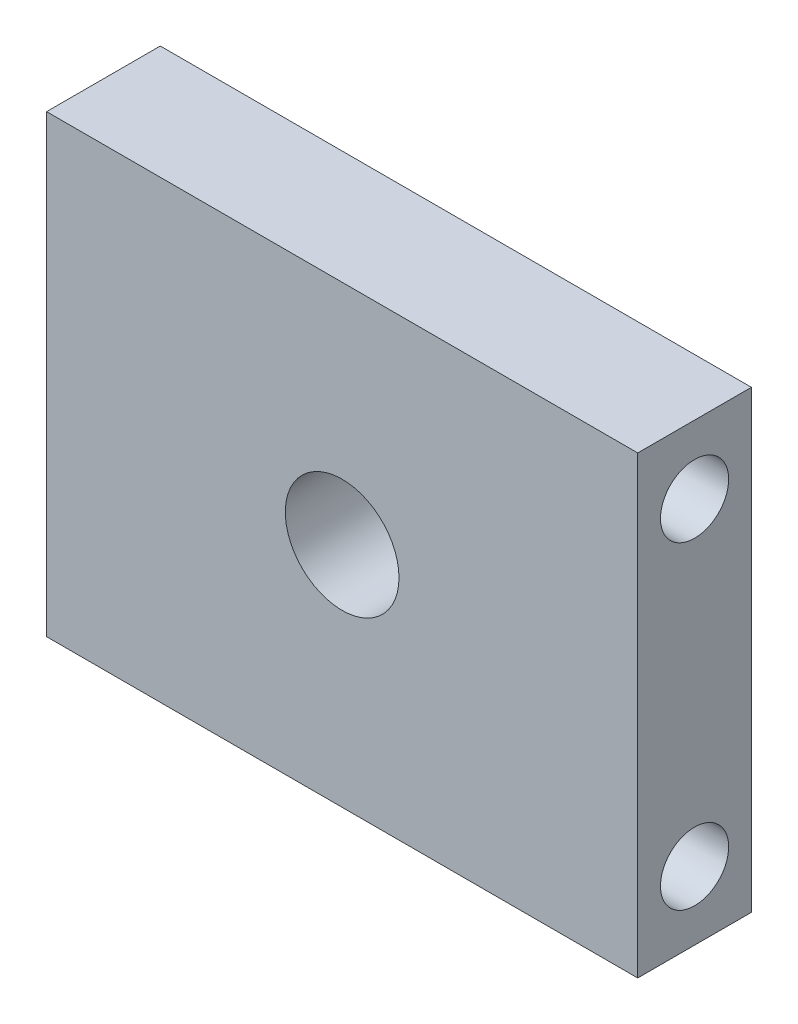
SolidWorks part; units mm, degrees
material "1060 Alloy"
ref_plane "前视基准面" through (0, 0, 0) normal (0, 0, 1) x (1, 0, 0)
ref_plane "上视基准面" through (0, 0, 0) normal (0, 1, 0) x (1, 0, 0)
ref_plane "右视基准面" through (0, 0, 0) normal (1, 0, 0) x (0, 0, -1)
sketch "Sketch1" plane through (0, 0, 0) normal (0, 0, 1) x (1, 0, 0)
  line L1 (-13, 10) -> (13, 10)
  line L2 (-13, 10) -> (-13, -10)
  line L3 (-13, -10) -> (13, -10)
  line L4 (13, 10) -> (13, -10)
  line L5 (-13, 10) -> (13, -10) construction
  line L6 (-13, -10) -> (13, 10) construction
  point P0 (0, 0)
  dimension "D1" = 26
  dimension "D2" = 20
extrude "Boss-Extrude1" add sketch "Sketch1" along normal blind 5
sketch "Sketch2" plane through (0, 0, 5) normal (0, 0, 1) x (1, 0, 0)
  circle A0 centre (0, 0) radius 2.5
extrude "Cut-Extrude1" cut sketch "Sketch2" against normal blind 5
sketch "Sketch3" plane through (-13, 0, 0) normal (-1, 0, 0) x (0, 0, 1)
  line L0 (2.5, 10) -> (2.5, -10) construction
  line L1 (5, 10) -> (0, 10) construction
  line L2 (5, -10) -> (0, -10) construction
  line L3 (0, 0) -> (5, 0) construction
  line L4 (5, 10) -> (5, -10) construction
  circle A0 centre (2.5, 7) radius 1.5
  circle A1 centre (2.5, -7) radius 1.5
  dimension "D1" = 7
extrude "Cut-Extrude2" cut sketch "Sketch3" against normal up to next
